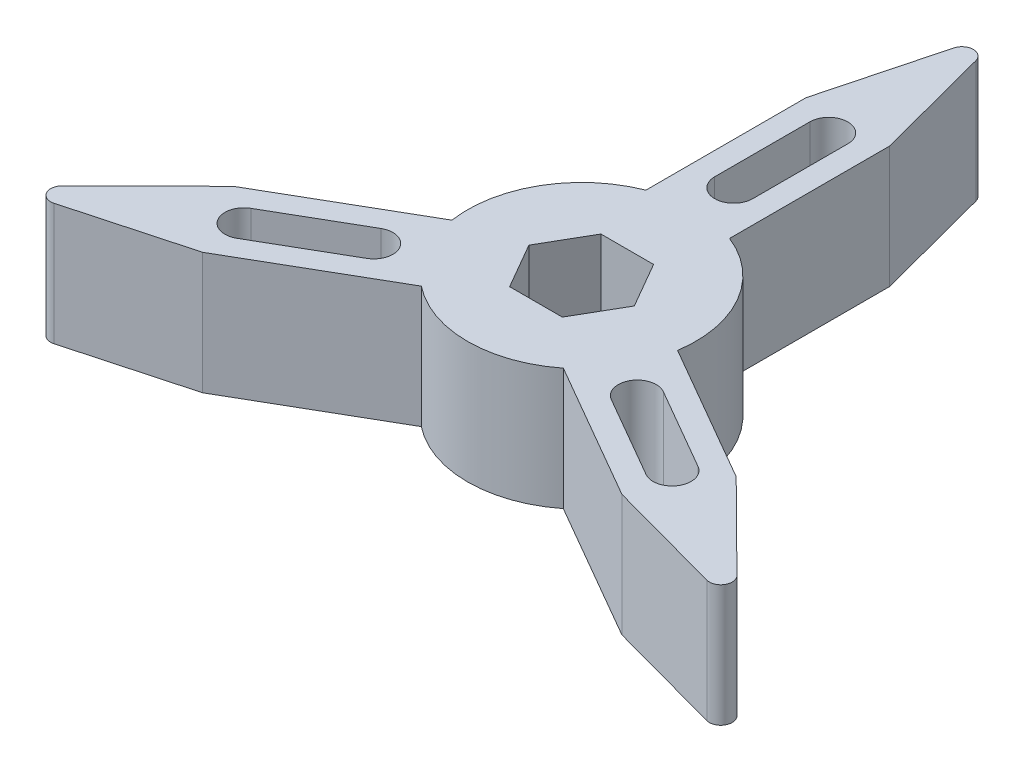
SolidWorks part; units mm, degrees
ref_plane "Front Plane" through (0, 0, 0) normal (0, 0, 1) x (1, 0, 0)
ref_plane "Top Plane" through (0, 0, 0) normal (0, 1, 0) x (1, 0, 0)
ref_plane "Right Plane" through (0, 0, 0) normal (1, 0, 0) x (0, 0, -1)
sketch "Sketch1" plane through (0, 0, 0) normal (0, 1, 0) x (1, 0, 0)
  line L0 (0, 2.5252) -> (0, 50002.5252) construction
  line L1 (13.8564, 0) -> (6.9282, 12)
  line L2 (6.9282, 12) -> (-6.9282, 12)
  line L3 (-6.9282, 12) -> (-13.8564, 0)
  line L4 (-13.8564, 0) -> (-6.9282, -12)
  line L5 (-6.9282, -12) -> (6.9282, -12)
  line L6 (6.9282, -12) -> (13.8564, 0)
  line L7 (0, 40) -> (0, 65) construction
  line L8 (-5, 40) -> (-5, 65)
  line L9 (5, 40) -> (5, 65)
  line L10 (0, 70) -> (11, 70) construction
  line L11 (11, 70) -> (11, 27.9106)
  line L12 (11, 70) -> (2.9012, 100.7638)
  line L13 (-11, 70) -> (-11, 27.9106)
  line L14 (-11, 70) -> (-2.9012, 100.7638)
  line L15 (55.1218, -44.5263) -> (18.6713, -23.4816)
  line L16 (66.1218, -25.4737) -> (29.6713, -4.429)
  line L17 (66.1218, -25.4737) -> (88.7145, -47.8694)
  line L18 (55.1218, -44.5263) -> (85.8134, -52.8943)
  line L19 (34.641, -20) -> (56.2917, -32.5) construction
  line L20 (37.141, -15.6699) -> (58.7917, -28.1699)
  line L21 (32.141, -24.3301) -> (53.7917, -36.8301)
  line L22 (-66.1218, -25.4737) -> (-29.6713, -4.429)
  line L23 (-55.1218, -44.5263) -> (-18.6713, -23.4816)
  line L24 (-55.1218, -44.5263) -> (-85.8134, -52.8943)
  line L25 (-66.1218, -25.4737) -> (-88.7145, -47.8694)
  line L26 (-34.641, -20) -> (-56.2917, -32.5) construction
  line L27 (-32.141, -24.3301) -> (-53.7917, -36.8301)
  line L28 (-37.141, -15.6699) -> (-58.7917, -28.1699)
  circle A0 centre (0, 0) radius 30
  circle A1 centre (0, 0) radius 12 construction
  arc A2 (-5, 40) -> (5, 40) centre (0, 40) ccw
  arc A3 (5, 65) -> (-5, 65) centre (0, 65) ccw
  arc A4 (2.9012, 100.7638) -> (-2.9012, 100.7638) centre (0, 100) ccw
  circle A5 centre (0, 0) radius 30
  arc A6 (85.8134, -52.8943) -> (88.7145, -47.8694) centre (86.6025, -50) ccw
  arc A7 (37.141, -15.6699) -> (32.141, -24.3301) centre (34.641, -20) ccw
  arc A8 (53.7917, -36.8301) -> (58.7917, -28.1699) centre (56.2917, -32.5) ccw
  circle A9 centre (0, 0) radius 30
  arc A10 (-88.7145, -47.8694) -> (-85.8134, -52.8943) centre (-86.6025, -50) ccw
  arc A11 (-32.141, -24.3301) -> (-37.141, -15.6699) centre (-34.641, -20) ccw
  arc A12 (-58.7917, -28.1699) -> (-53.7917, -36.8301) centre (-56.2917, -32.5) ccw
  point P14 (0, 52.5)
  point P22 (5.5, 70)
  point P33 (45.4663, -26.25)
  point P48 (-45.4663, -26.25)
  point P60 (0, 0)
  dimension "D1" = 24
  dimension "D2" = 60
  dimension "D8" = 6
  dimension "D3" = 10
  dimension "D4" = 25
  dimension "D5" = 40
  dimension "D6" = 22
  dimension "D7" = 70
  dimension "D9" = 30
  dimension "D10" = 3
extrude "Boss-Extrude1" add sketch "Sketch1" along normal blind 32 contours L12 A4 L14 L13 A0 L11 A3 L9 A2 L8 | A0 L6 L5 L4 L3 L2 L1 | L18 A6 L17 L16 A0 L15 A8 L21 A7 L20 | L25 A10 L24 L23 A0 L22 A12 L28 A11 L27
